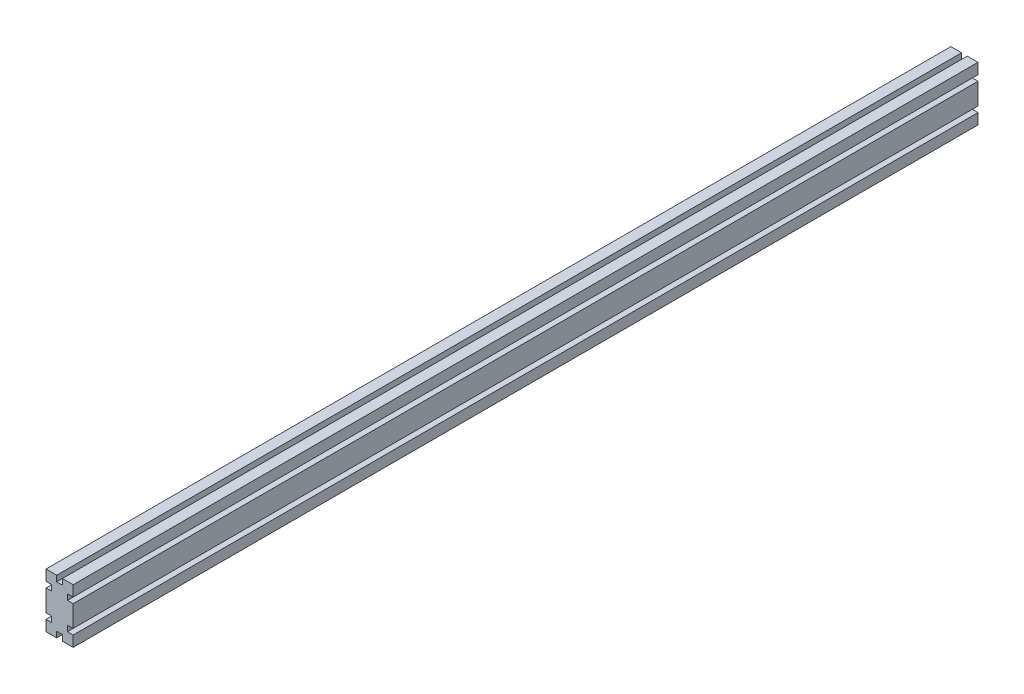
SolidWorks part; units mm, degrees
ref_plane "Front Plane" through (0, 0, 0) normal (0, 0, 1) x (1, 0, 0)
ref_plane "Top Plane" through (0, 0, 0) normal (0, 1, 0) x (1, 0, 0)
ref_plane "Right Plane" through (0, 0, 0) normal (1, 0, 0) x (0, 0, -1)
sketch "Sketch1" plane through (0, 0, 0) normal (0, 0, 1) x (1, 0, 0)
  line L0 (-19.05, -38.1) -> (-4, -38.1)
  line L1 (-4, -38.1) -> (-4, -30.1)
  line L2 (-4, -30.1) -> (4, -30.1)
  line L3 (4, -30.1) -> (4, -38.1)
  line L4 (4, -38.1) -> (19.05, -38.1)
  line L5 (19.05, -38.1) -> (19.05, -23.05)
  line L6 (19.05, -23.05) -> (11.05, -23.05)
  line L7 (11.05, -23.05) -> (11.05, -15.05)
  line L8 (11.05, -15.05) -> (19.05, -15.05)
  line L9 (19.05, -15.05) -> (19.05, 15.05)
  line L10 (19.05, 15.05) -> (11.05, 15.05)
  line L11 (11.05, 15.05) -> (11.05, 23.05)
  line L12 (11.05, 23.05) -> (19.05, 23.05)
  line L13 (19.05, 23.05) -> (19.05, 38.1)
  line L14 (19.05, 38.1) -> (4, 38.1)
  line L15 (4, 38.1) -> (4, 30.1)
  line L16 (4, 30.1) -> (-4, 30.1)
  line L17 (-4, 30.1) -> (-4, 38.1)
  line L18 (-4, 38.1) -> (-19.05, 38.1)
  line L19 (-19.05, 38.1) -> (-19.05, 23.05)
  line L20 (-19.05, 23.05) -> (-11.05, 23.05)
  line L21 (-11.05, 23.05) -> (-11.05, 15.05)
  line L22 (-11.05, 15.05) -> (-19.05, 15.05)
  line L23 (-19.05, 15.05) -> (-19.05, -15.05)
  line L24 (-19.05, -15.05) -> (-11.05, -15.05)
  line L25 (-11.05, -15.05) -> (-11.05, -23.05)
  line L26 (-11.05, -23.05) -> (-19.05, -23.05)
  line L27 (-19.05, -23.05) -> (-19.05, -38.1)
extrude "Profile" add sketch "Sketch1" along normal blind 1270
equation "\"length\" = 1270.0mm"
equation "\"D1@Profile\" = \"length\""
